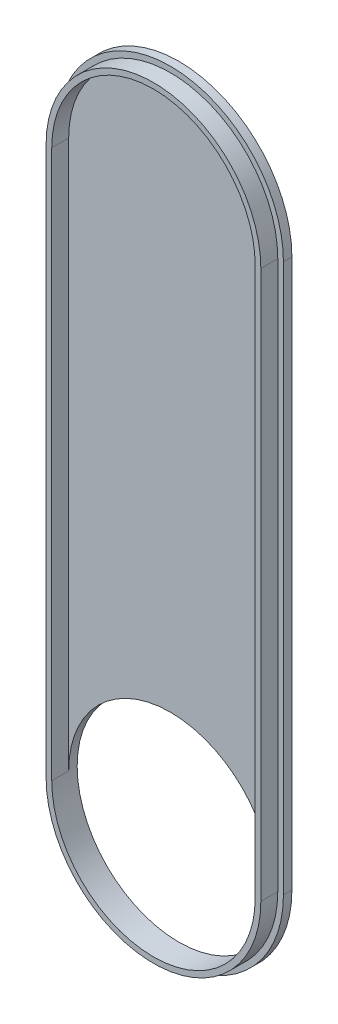
SolidWorks part; units mm, degrees
material "PLA"
ref_plane "Front Plane" through (0, 0, 0) normal (0, 0, 1) x (1, 0, 0)
ref_plane "Top Plane" through (0, 0, 0) normal (0, 1, 0) x (1, 0, 0)
ref_plane "Right Plane" through (0, 0, 0) normal (1, 0, 0) x (0, 0, -1)
sketch "Sketch3" plane through (0, 0, 0) normal (0, 0, 1) x (1, 0, 0)
  line L0 (-20, 0) -> (-20, -97)
  line L1 (20, 0) -> (20, -97)
  arc A0 (20, 0) -> (-20, 0) centre (0, 0) ccw
  arc A1 (-20, -97) -> (20, -97) centre (0, -97) ccw
  dimension "D1" = 40
  dimension "D3" = 20
  dimension "D2" = 97
extrude "Boss-Extrude1" add sketch "Sketch3" along normal blind 1.5
sketch "Sketch5" plane through (0, 0, 1.5) normal (0, 0, 1) x (1, 0, 0)
  line L5 (-18, 0) -> (-18, -97)
  line L6 (18, -97) -> (18, 0)
  line L7 (-19, 0) -> (-19, -97)
  line L8 (19, -97) -> (19, 0)
  line L9 (-19, 0) -> (-19, -97)
  line L10 (19, -97) -> (19, 0)
  arc A5 (18, 0) -> (-18, 0) centre (0, 0) ccw
  arc A6 (-18, -97) -> (18, -97) centre (0, -97) ccw
  arc A7 (-19, -97) -> (19, -97) centre (0, -97) ccw
  arc A8 (19, 0) -> (-19, 0) centre (0, 0) ccw
  arc A9 (-19, -97) -> (19, -97) centre (0, -97) ccw
  arc A10 (19, 0) -> (-19, 0) centre (0, 0) ccw
  dimension "D1" = 1
  dimension "D2" = 1
extrude "Boss-Extrude2" add sketch "Sketch5" along normal blind 3
sketch "Sketch6" plane through (0, 0, 0) normal (0, 0, -1) x (-1, 0, 0)
  circle A0 centre (0, -97) radius 18
  dimension "D1" = 36
extrude "Cut-Extrude1" cut sketch "Sketch6" against normal through all
